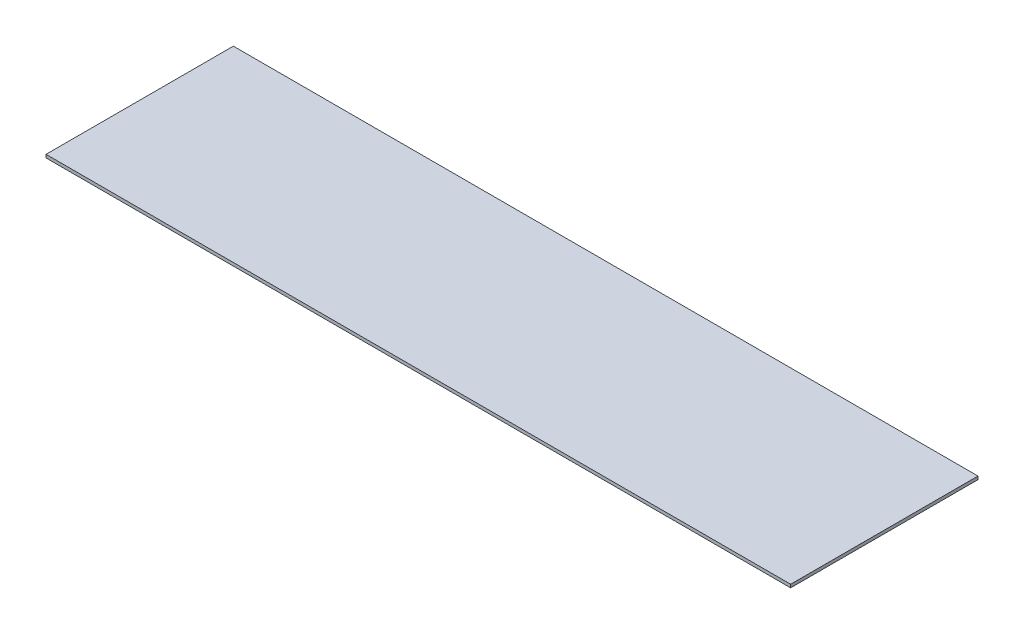
SolidWorks part; units mm, degrees
ref_plane "Спереди" through (0, 0, 0) normal (0, 0, 1) x (1, 0, 0)
ref_plane "Сверху" through (0, 0, 0) normal (0, 1, 0) x (1, 0, 0)
ref_plane "Справа" through (0, 0, 0) normal (1, 0, 0) x (0, 0, -1)
sketch "Эскиз1" plane through (0, 0, 0) normal (0, 1, 0) x (1, 0, 0)
  line L1 (1069, -269) -> (-1069, -269)
  line L2 (1069, -269) -> (1069, 269)
  line L3 (1069, 269) -> (-1069, 269)
  line L4 (-1069, -269) -> (-1069, 269)
  line L5 (1069, -269) -> (-1069, 269) construction
  line L6 (1069, 269) -> (-1069, -269) construction
  point P0 (0, 0)
  dimension "D1" = 2138
  dimension "D2" = 538
extrude "Бобышка-Вытянуть1" add sketch "Эскиз1" along normal blind 9
